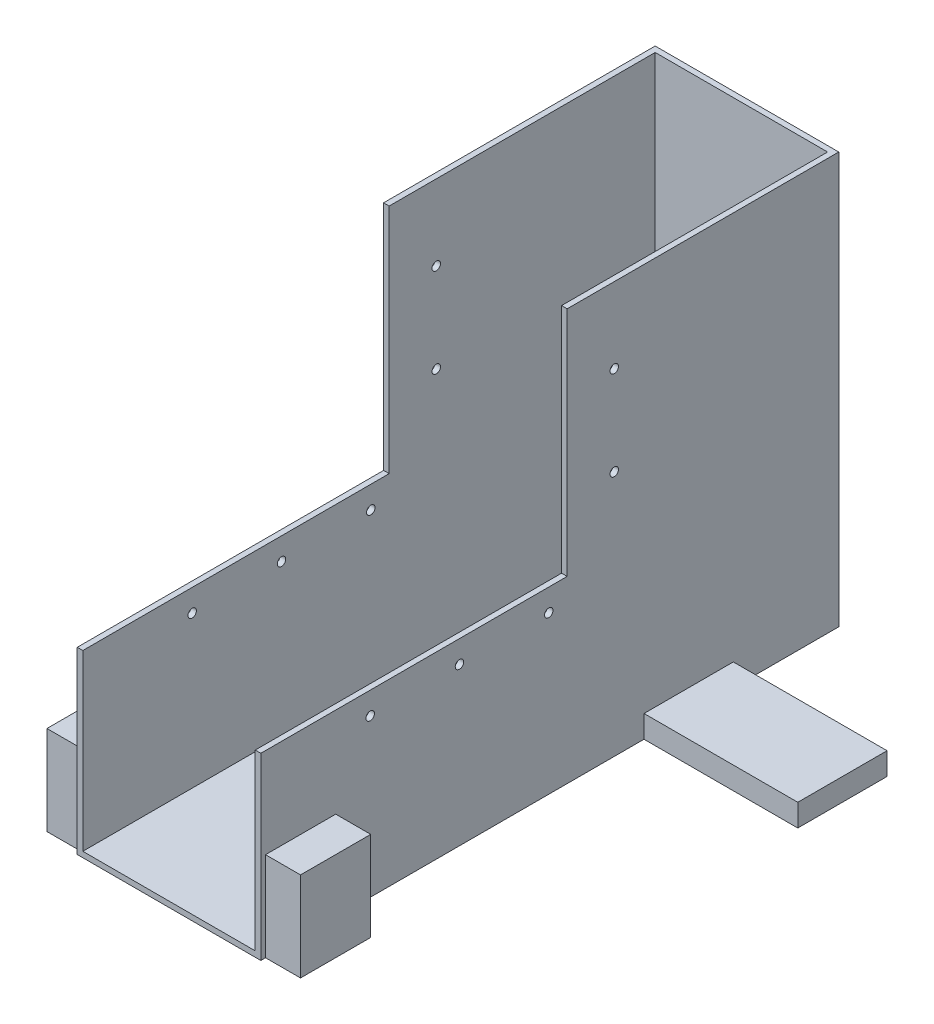
SolidWorks part; units mm, degrees
ref_plane "Front Plane" through (0, 0, 0) normal (0, 0, 1) x (1, 0, 0)
ref_plane "Top Plane" through (0, 0, 0) normal (0, 1, 0) x (1, 0, 0)
ref_plane "Right Plane" through (0, 0, 0) normal (1, 0, 0) x (0, 0, -1)
sketch "Sketch15" plane through (0, 0, 0) normal (1, 0, 0) x (0, 0, -1)
  line B0 (0, 0) -> (-657.6158, 0)
  line B1 (0, 0) -> (0, 467.9127)
  line B2 (-657.6158, 0) -> (-657.6158, 204.2049)
  line B3 (0, 467.9127) -> (-309.0338, 467.9127)
  line B4 (-309.0338, 204.2049) -> (-657.6158, 204.2049)
  line B5 (-309.0338, 204.2049) -> (-309.0338, 467.9127)
sketch_block_instance "frameSideview-1"
sketch_block "Block1"
extrude "Boss-Extrude1" add sketch "Sketch15" against normal blind 6.35
sketch "Sketch16" plane through (0, 0, 0) normal (0, 1, 0) x (1, 0, 0)
  line B0 (0, -685.8) -> (196.1896, -685.8)
  line B1 (0, -685.8) -> (0, 0)
  line B2 (196.1896, -685.8) -> (196.1896, 0)
  line B3 (0, -685.8) -> (196.1896, 0) construction
  line B4 (0, 0) -> (196.1896, -685.8) construction
sketch_block_instance "Drivebase_gearbox_Gap-1"
sketch_block "Drivebase_gearbox_Gap"
sketch "Sketch17" plane through (0, 0, 0) normal (0, 1, 0) x (1, 0, 0)
  line L0 (196.1896, -685.8) -> (196.1896, 0) construction
  line L1 (0, 0) -> (196.1896, 0)
  line L2 (0, 0) -> (0, -657.6158)
  line L3 (0, -657.6158) -> (196.1896, -657.6158)
  line L4 (196.1896, 0) -> (196.1896, -657.6158)
  line L5 (-6.35, -657.6158) -> (0, -657.6158) construction
extrude "Boss-Extrude2" add sketch "Sketch17" along normal blind 6.35
ref_plane "Plane1" through (98.0948, 0, 0) normal (1, 0, 0) x (0, 0, -1)
mirror "Mirror1" about plane through (98.0948, 0, 0) normal (1, 0, 0) of "Boss-Extrude1"
sketch "Sketch18" plane through (0, 0, 0) normal (0, 0, -1) x (-1, 0, 0)
  line L1 (-202.5396, 467.9127) -> (6.35, 467.9127)
  line L2 (-202.5396, 467.9127) -> (-202.5396, 0)
  line L3 (-202.5396, 0) -> (6.35, 0)
  line L4 (6.35, 467.9127) -> (6.35, 0)
extrude "Boss-Extrude3" add sketch "Sketch18" against normal blind 6.35
sketch "Sketch19" plane through (0, 0, 0) normal (0, 1, 0) x (1, 0, 0)
  line L1 (98.0948, -253.8595) -> (98.0948, 253.8595) construction
  line B0 (98.0948, -323.1859) -> (98.0948, 49676.8141) construction
  line B1 (-181.3052, -119.9859) -> (377.4948, -119.9859)
  line B2 (-181.3052, -119.9859) -> (-181.3052, -221.5859)
  line B3 (-181.3052, -221.5859) -> (377.4948, -221.5859)
  line B4 (377.4948, -119.9859) -> (377.4948, -221.5859)
  line B5 (-46.1772, -572.3724) -> (242.3668, -572.3724)
  line B6 (-46.1772, -572.3724) -> (-46.1772, -652.2613)
  line B7 (-46.1772, -652.2613) -> (242.3668, -652.2613)
  line B8 (242.3668, -572.3724) -> (242.3668, -652.2613)
sketch_block_instance "frameTopView-1"
sketch_block "frameTopView"
sketch "Sketch20" plane through (0, 0, 0) normal (0, 1, 0) x (1, 0, 0)
  line L0 (-181.3052, -119.9859) -> (377.4948, -119.9859) construction
  line L1 (-181.3052, -221.5859) -> (-6.35, -221.5859)
  line L2 (-181.3052, -221.5859) -> (-181.3052, -119.9859)
  line L3 (-181.3052, -119.9859) -> (-6.35, -119.9859)
  line L4 (-6.35, -221.5859) -> (-6.35, -119.9859)
  line L5 (-6.35, 0) -> (-6.35, -309.0338) construction
  line L6 (-181.3052, -221.5859) -> (377.4948, -221.5859) construction
  line L7 (377.4948, -119.9859) -> (202.5396, -119.9859)
  line L8 (377.4948, -119.9859) -> (377.4948, -221.5859)
  line L9 (377.4948, -221.5859) -> (202.5396, -221.5859)
  line L10 (202.5396, -119.9859) -> (202.5396, -221.5859)
  line L11 (202.5396, 0) -> (202.5396, -309.0338) construction
extrude "Boss-Extrude4" add sketch "Sketch20" along normal blind 25.4
sketch "Sketch22" plane through (0, 0, 0) normal (0, 1, 0) x (1, 0, 0)
  line L0 (-46.1772, -652.2613) -> (242.3668, -652.2613) construction
  line L1 (-46.1772, -572.3724) -> (-6.35, -572.3724)
  line L2 (-46.1772, -572.3724) -> (-46.1772, -652.2613)
  line L3 (-46.1772, -652.2613) -> (-6.35, -652.2613)
  line L4 (-6.35, -572.3724) -> (-6.35, -652.2613)
  line L5 (-6.35, -309.0338) -> (-6.35, -657.6158) construction
  line L6 (202.5396, -309.0338) -> (202.5396, -657.6158) construction
  line L7 (242.3668, -572.3724) -> (202.5396, -572.3724)
  line L8 (242.3668, -572.3724) -> (242.3668, -652.2613)
  line L9 (242.3668, -652.2613) -> (202.5396, -652.2613)
  line L10 (202.5396, -572.3724) -> (202.5396, -652.2613)
extrude "Boss-Extrude5" add sketch "Sketch22" along normal blind 101.6
sketch "Sketch25" plane through (-6.35, 0, 0) normal (-1, 0, 0) x (0, 0, 1)
  line L0 (255.4398, 467.9127) -> (255.4398, 0)
  line L1 (0, 467.9127) -> (309.0338, 467.9127) construction
  line L2 (572.3724, 0) -> (221.5859, 0) construction
  line L3 (0, 178.8049) -> (657.6158, 178.8049)
  line L4 (0, 0) -> (0, 467.9127) construction
  line L5 (657.6158, 204.2049) -> (657.6158, 0) construction
  line L6 (309.0338, 467.9127) -> (309.0338, 204.2049) construction
  line L7 (309.0338, 204.2049) -> (657.6158, 204.2049) construction
  circle A0 centre (533.1558, 178.8049) radius 4.826
  circle A1 centre (431.5558, 178.8049) radius 4.826
  circle A2 centre (329.9558, 178.8049) radius 4.826
  circle A3 centre (255.4398, 280.4607) radius 4.826
  circle A4 centre (255.4398, 382.0607) radius 4.826
  point P16 (255.4398, 280.4607)
  point P17 (255.4398, 467.9127)
  point P18 (255.4398, 382.0607)
  point P19 (329.9558, 178.8049)
  point P20 (431.5558, 178.8049)
  point P21 (533.1558, 178.8049)
  point P32 (0, 0)
  point P33 (0, 0)
  point P34 (0, 0)
  dimension "D8" = 9.652
  dimension "D9" = 9.652
  dimension "D10" = 9.652
  dimension "D11" = 9.652
  dimension "D12" = 9.652
  dimension "D1" = 53.594
  dimension "D2" = 25.4
  dimension "D3" = 85.852
  dimension "D4" = 101.6
  dimension "D5" = 124.46
  dimension "D6" = 101.6
  dimension "D7" = 101.6
extrude "Cut-Extrude1" cut sketch "Sketch25" against normal blind 6.35 contours A0 | A1 | A2 | A3 | A4
mirror "Mirror2" about plane through (98.0948, 0, 0) normal (1, 0, 0) of "Cut-Extrude1"
